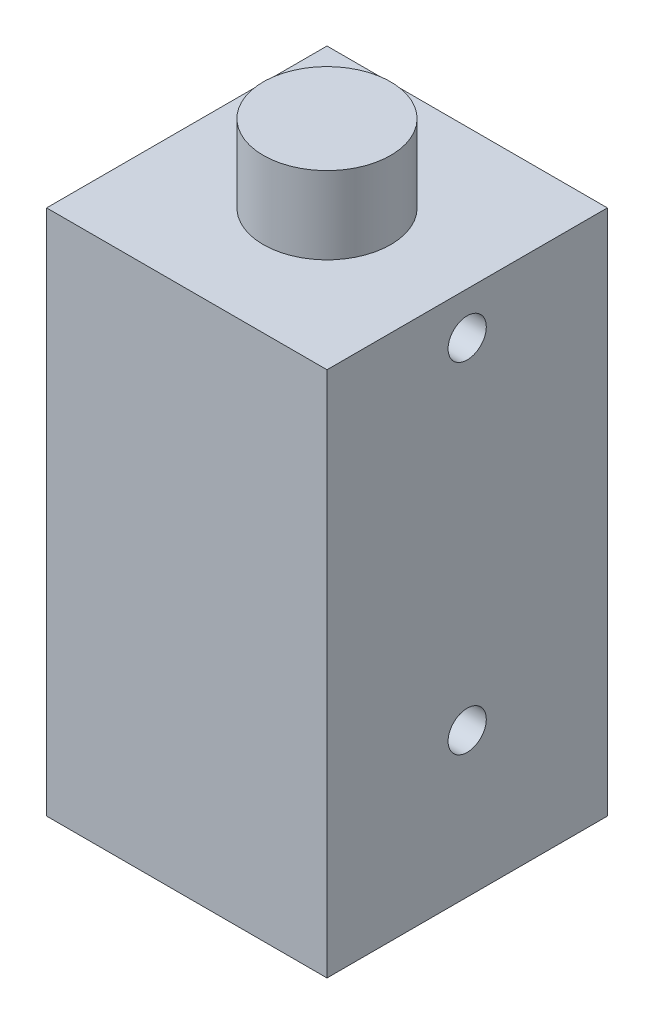
SolidWorks part; units mm, degrees
ref_plane "Front" through (0, 0, 0) normal (0, 0, 1) x (1, 0, 0)
ref_plane "Top" through (0, 0, 0) normal (0, 1, 0) x (1, 0, 0)
ref_plane "Right" through (0, 0, 0) normal (1, 0, 0) x (0, 0, -1)
sketch "Sketch1" plane through (0, 0, 0) normal (0, 1, 0) x (1, 0, 0)
  line L1 (-16.5, -16.5) -> (16.5, -16.5)
  line L2 (-16.5, -16.5) -> (-16.5, 16.5)
  line L3 (-16.5, 16.5) -> (16.5, 16.5)
  line L4 (16.5, -16.5) -> (16.5, 16.5)
  line L5 (-16.5, -16.5) -> (16.5, 16.5) construction
  line L6 (-16.5, 16.5) -> (16.5, -16.5) construction
  point P0 (0, 0)
  dimension "D1" = 33
  dimension "D2" = 33
extrude "Boss-Extrude1" add sketch "Sketch1" along normal blind 62
sketch "Sketch2" plane through (0, 62, 0) normal (0, 1, 0) x (1, 0, 0)
  circle A0 centre (0, 0) radius 7.5
  dimension "D1" = 15
extrude "Boss-Extrude2" add sketch "Sketch2" along normal blind 9.1
sketch "Sketch3" plane through (16.5, 0, 0) normal (1, 0, 0) x (0, 0, -1)
  line L0 (0, 62) -> (0, 0) construction
  line L1 (-16.5, 62) -> (16.5, 62) construction
  circle A0 centre (0, 57) radius 2.25
  circle A1 centre (0, 17) radius 2.25
  dimension "D2" = 4.5
  dimension "D4" = 4.5
  dimension "D1" = 5
  dimension "D3" = 45
extrude "Cut-Extrude1" cut sketch "Sketch3" against normal blind 9.1
